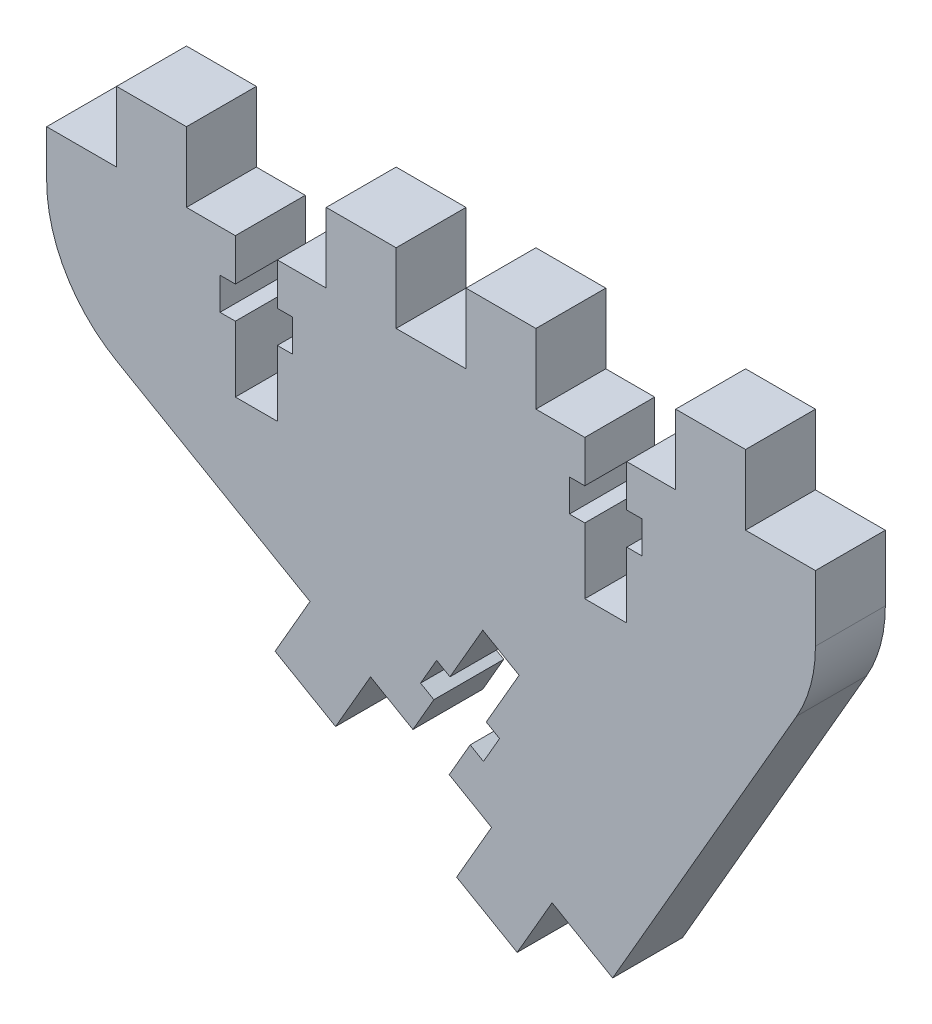
SolidWorks part; units mm, degrees
ref_plane "Plan de face" through (0, 0, 0) normal (0, 0, 1) x (1, 0, 0)
ref_plane "Plan de dessus" through (0, 0, 0) normal (0, 1, 0) x (1, 0, 0)
ref_plane "Plan de droite" through (0, 0, 0) normal (1, 0, 0) x (0, 0, -1)
sketch "Esquisse1" plane through (0, 0, 0) normal (0, 0, 1) x (1, 0, 0)
  line L1 (0, 0) -> (0, -30.9586) construction
  line L2 (-8.6603, 5) -> (-12.9904, 7.5)
  line L3 (-27.5, 15.8771) -> (-27.5, 25)
  line L4 (-12.9904, 7.5) -> (-27.5, 15.8771)
  line L5 (-2.5, 25) -> (2.5, 25)
  line L6 (8.6603, -5) -> (12.9904, -7.5)
  line L7 (12.9904, -7.5) -> (27.5, 17.6314)
  line L8 (27.5, 17.6314) -> (27.5, 25)
  line L9 (27.5, 25) -> (22.5, 25)
  line L10 (-22.5, 25) -> (-27.5, 25)
  line B0 (-0.7517, 3.8981) -> (0.3983, 5.8899)
  line B1 (3.949, 3.8399) -> (6.299, 7.9103)
  line B2 (3.701, 9.4103) -> (1.351, 5.3399)
  line B3 (0.3983, 5.8899) -> (1.351, 5.3399)
  line B4 (0, 0) -> (5.6104, 9.7175) construction
  line B5 (-1.299, 0.75) -> (-4.3301, 2.5)
  line B6 (-6.8301, -1.8301) -> (-11.1603, 0.6699)
  line B7 (-11.1603, 0.6699) -> (-8.6603, 5)
  line B8 (-6.8301, -1.8301) -> (-4.3301, 2.5)
  line B9 (1.299, -0.75) -> (4.3301, -2.5)
  line B10 (4.3301, -2.5) -> (1.8301, -6.8301)
  line B11 (1.8301, -6.8301) -> (6.1603, -9.3301)
  line B12 (6.1603, -9.3301) -> (8.6603, -5)
  line B13 (-1.299, 0.75) -> (1.299, -0.75) construction
  line B14 (1.299, -0.75) -> (2.799, 1.8481)
  line B15 (3.949, 3.8399) -> (4.9017, 3.2899)
  line B16 (3.7517, 1.2981) -> (2.799, 1.8481)
  line B17 (6.299, 7.9103) -> (3.701, 9.4103)
  line B18 (0.201, 3.3481) -> (-0.7517, 3.8981)
  line B19 (4.9017, 3.2899) -> (3.7517, 1.2981)
  line B20 (0.201, 3.3481) -> (-1.299, 0.75)
  line B21 (5, 8.6603) -> (0, 0) construction
  line B22 (15.1, 22) -> (15.1, 19.7)
  line B23 (11, 19.7) -> (11, 15)
  line B24 (14, 15) -> (14, 19.7)
  line B25 (15.1, 19.7) -> (14, 19.7)
  line B26 (12.5, 25) -> (12.5, 13.7792) construction
  line B27 (14, 25) -> (17.5, 25)
  line B28 (17.5, 30) -> (22.5, 30)
  line B29 (22.5, 30) -> (22.5, 25)
  line B30 (17.5, 30) -> (17.5, 25)
  line B31 (11, 25) -> (7.5, 25)
  line B32 (7.5, 25) -> (7.5, 30)
  line B33 (7.5, 30) -> (2.5, 30)
  line B34 (2.5, 30) -> (2.5, 25)
  line B35 (14, 25) -> (11, 25) construction
  line B36 (11, 25) -> (11, 22)
  line B37 (11, 19.7) -> (9.9, 19.7)
  line B38 (9.9, 22) -> (11, 22)
  line B39 (11, 15) -> (14, 15)
  line B40 (14, 22) -> (15.1, 22)
  line B41 (9.9, 19.7) -> (9.9, 22)
  line B42 (14, 22) -> (14, 25)
  line B43 (12.5, 15) -> (12.5, 25) construction
  line B44 (-15.1, 22) -> (-15.1, 19.7)
  line B45 (-11, 19.7) -> (-11, 15)
  line B46 (-14, 15) -> (-14, 19.7)
  line B47 (-15.1, 19.7) -> (-14, 19.7)
  line B48 (-12.5, 25) -> (-12.5, 13.7792) construction
  line B49 (-14, 25) -> (-17.5, 25)
  line B50 (-17.5, 30) -> (-22.5, 30)
  line B51 (-22.5, 30) -> (-22.5, 25)
  line B52 (-17.5, 30) -> (-17.5, 25)
  line B53 (-11, 25) -> (-7.5, 25)
  line B54 (-7.5, 25) -> (-7.5, 30)
  line B55 (-7.5, 30) -> (-2.5, 30)
  line B56 (-2.5, 30) -> (-2.5, 25)
  line B57 (-14, 25) -> (-11, 25) construction
  line B58 (-11, 25) -> (-11, 22)
  line B59 (-11, 19.7) -> (-9.9, 19.7)
  line B60 (-9.9, 22) -> (-11, 22)
  line B61 (-11, 15) -> (-14, 15)
  line B62 (-14, 22) -> (-15.1, 22)
  line B63 (-9.9, 19.7) -> (-9.9, 22)
  line B64 (-14, 22) -> (-14, 25)
  line B65 (-12.5, 15) -> (-12.5, 25) construction
  dimension "D1" = 5
  dimension "D2" = 30
  dimension "D3" = 5
  dimension "D4" = 25
sketch_block_instance "Insert M3 plots ep 5mm-1"
sketch_block "Insert M3 plots ep 5mm" parameters "D1"=10, "D2"=5, "D3"=5
sketch_block_instance "Decoupe Insert M3-4"
sketch_block "Decoupe Insert M3" parameters "D1"=5.2, "D2"=3, "D3"=2.3, "D4"=3, "D5"=10
sketch_block_instance "Insert M3 plots ep 5mm-3"
sketch_block_instance "Insert M3 plots ep 5mm-4"
extrude "Boss.-Extru.1" add sketch "Esquisse1" along normal blind 5
fillet "Congé1" radius 10 2 edges at (-27.5, 15.8771, 2.5) (27.5, 17.6314, 2.5)
